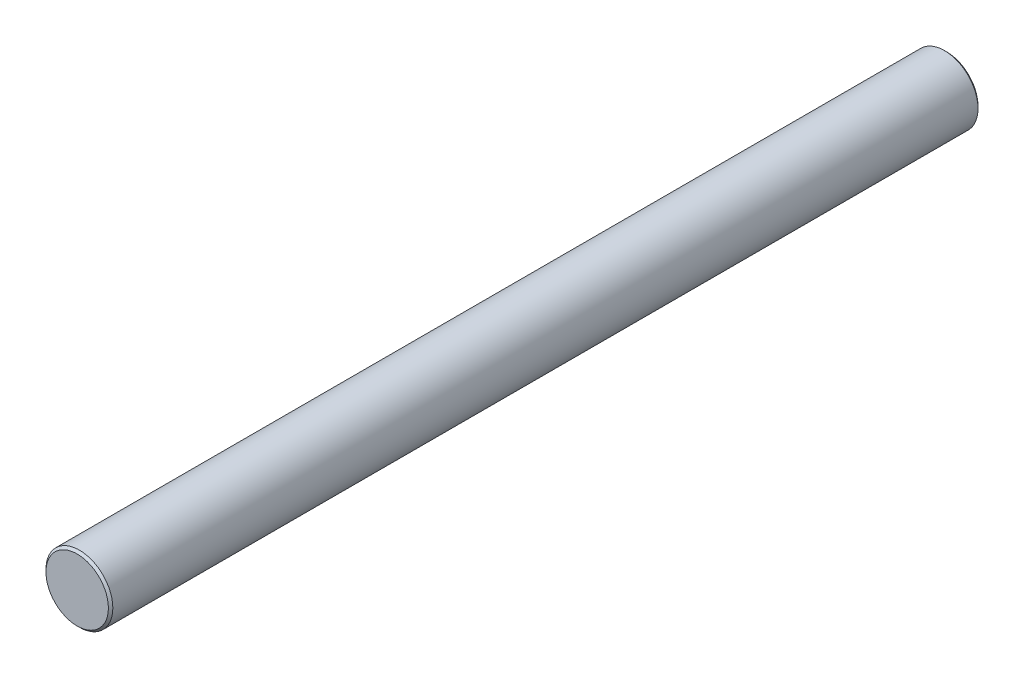
SolidWorks part; units mm, degrees
ref_plane "Plan de face" through (0, 0, 0) normal (0, 0, 1) x (1, 0, 0)
ref_plane "Plan de dessus" through (0, 0, 0) normal (0, 1, 0) x (1, 0, 0)
ref_plane "Plan de droite" through (0, 0, 0) normal (1, 0, 0) x (0, 0, -1)
sketch "Esquisse1" plane through (0, 0, 0) normal (0, 0, 1) x (1, 0, 0)
  circle A0 centre (0, 0) radius 1.5
  dimension "D1" = 3
extrude "Boss.-Extru.1" add sketch "Esquisse1" along normal blind 39
chamfer "Chanfrein1" distance 0.1 angle 45 2 edges at (1.5, 0, 39) (1.5, 0, 0)
